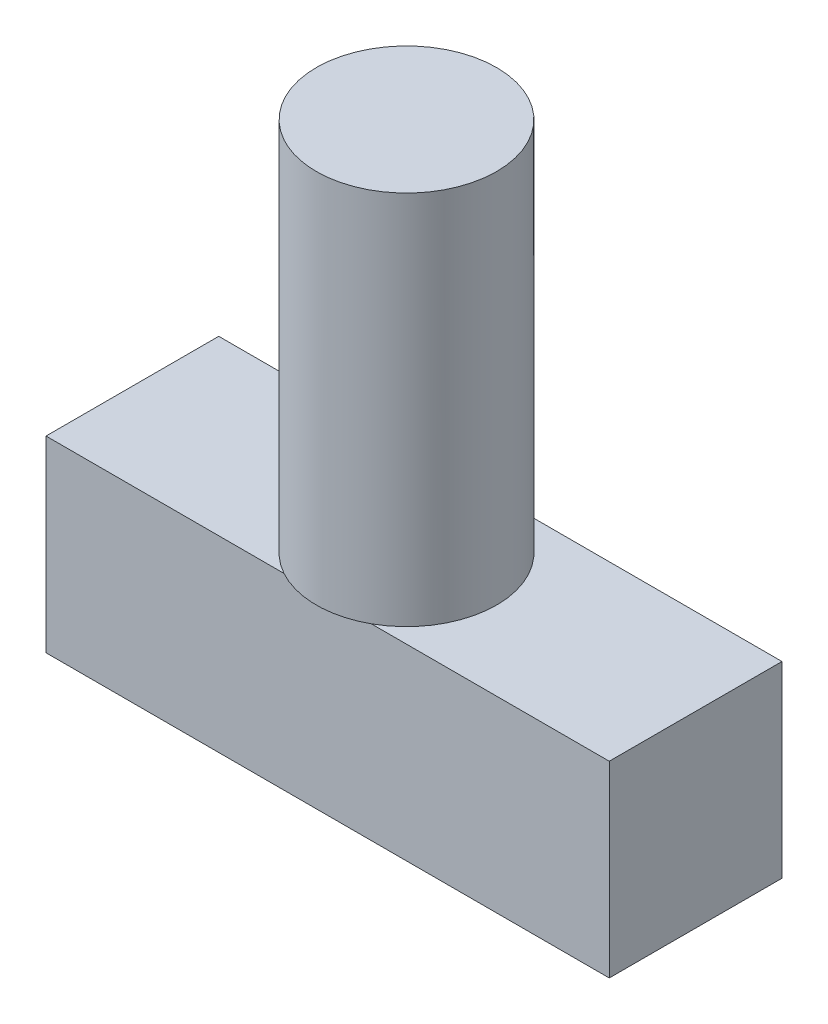
SolidWorks part; units mm, degrees
ref_plane "Front Plane" through (0, 0, 0) normal (0, 0, 1) x (1, 0, 0)
ref_plane "Top Plane" through (0, 0, 0) normal (0, 1, 0) x (1, 0, 0)
ref_plane "Right Plane" through (0, 0, 0) normal (1, 0, 0) x (0, 0, -1)
sketch "Sketch1" plane through (0, 0, 0) normal (0, 1, 0) x (1, 0, 0)
  line L1 (-7.5, -2.1) -> (7.5, -2.1)
  line L2 (-7.5, -2.1) -> (-7.5, 2.5)
  line L3 (-7.5, 2.5) -> (7.5, 2.5)
  line L4 (7.5, -2.1) -> (7.5, 2.5)
  point P0 (0, 0)
  dimension "D1" = 4.6
  dimension "D2" = 15
extrude "Boss-Extrude1" add sketch "Sketch1" along normal blind 5
sketch "Sketch2" plane through (0, 5, 0) normal (0, 1, 0) x (1, 0, 0)
  circle A0 centre (0, 0) radius 2.4
  dimension "D1" = 4.8
extrude "Boss-Extrude2" add sketch "Sketch2" along normal blind 10
